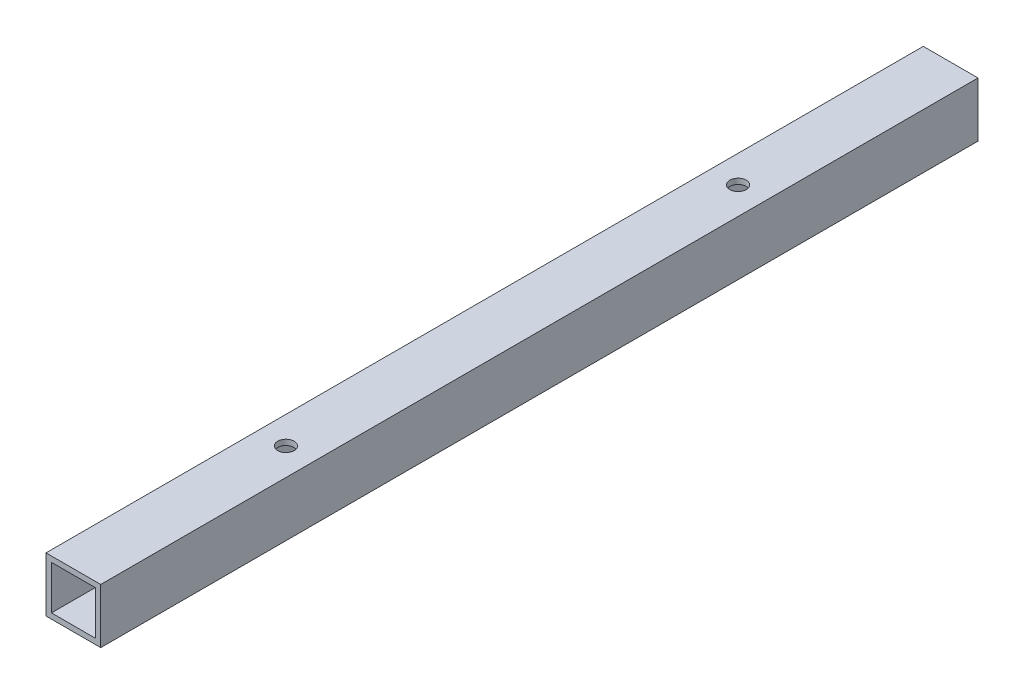
SolidWorks part; units mm, degrees
material "Thornel Mat VMA"
ref_plane "前视基准面" through (0, 0, 0) normal (0, 0, 1) x (1, 0, 0)
ref_plane "上视基准面" through (0, 0, 0) normal (0, 1, 0) x (1, 0, 0)
ref_plane "右视基准面" through (0, 0, 0) normal (1, 0, 0) x (0, 0, -1)
sketch "草图1" plane through (0, 0, 0) normal (0, 0, 1) x (1, 0, 0)
  line L1 (5, 5) -> (-5, 5)
  line L2 (5, 5) -> (5, -5)
  line L3 (5, -5) -> (-5, -5)
  line L4 (-5, 5) -> (-5, -5)
  line L5 (5, 5) -> (-5, -5) construction
  line L6 (5, -5) -> (-5, 5) construction
  line L7 (4, 4) -> (-4, 4)
  line L8 (4, 4) -> (4, -4)
  line L9 (4, -4) -> (-4, -4)
  line L10 (-4, 4) -> (-4, -4)
  line L11 (4, 4) -> (-4, -4) construction
  line L12 (4, -4) -> (-4, 4) construction
  point P0 (0, 0)
  point P6 (0, 0)
  dimension "D1" = 10
  dimension "D2" = 1
extrude "凸台-拉伸1" add sketch "草图1" along normal mid plane 160.31
hole_wizard "孔1" positions "草图2" profile "草图3" legacy end condition through all
sketch "草图2" plane through (0, -5, 0) normal (0, -1, 0) x (-1, 0, 0)
  point P0 (0.0035, -41.3127)
  point P3 (0.0035, 41.3127)
sketch "草图3" plane through (-0.0035, -5, 41.3127) normal (1, 0, 0) x (0, 0, -1)
  line L0 (0, 0) -> (0, 10)
  line L1 (0, 10) -> (1.5, 10)
  line L2 (1.5, 10) -> (1.5, 0)
  line L3 (1.5, 0) -> (0, 0)
  line L4 (0, 110) -> (0, -10) construction
  dimension "直径" = 3
  dimension "深度" = 10
